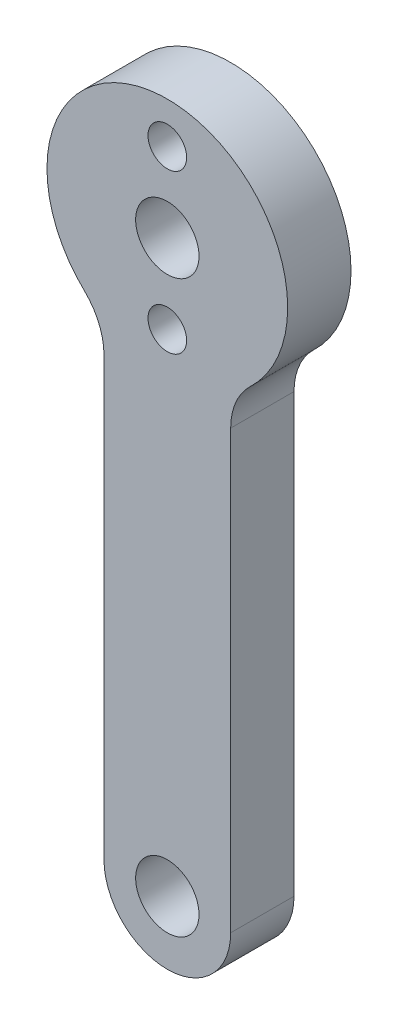
SolidWorks part; units mm, degrees
material "Thornel Mat VMA"
ref_plane "前视基准面" through (0, 0, 0) normal (0, 0, 1) x (1, 0, 0)
ref_plane "上视基准面" through (0, 0, 0) normal (0, 1, 0) x (1, 0, 0)
ref_plane "右视基准面" through (0, 0, 0) normal (1, 0, 0) x (0, 0, -1)
sketch "草图1" plane through (0, 0, 0) normal (0, 0, 1) x (1, 0, 0)
  line L0 (0, 0) -> (0, -45) construction
  line L1 (5, -8.0777) -> (5, -45)
  line L2 (-5, -8.0777) -> (-5, -45)
  arc A0 (5, -8.0777) -> (-5, -8.0777) centre (0, 0) ccw
  arc A2 (-5, -45) -> (5, -45) centre (0, -45) ccw
  point P3 (0, -25)
  dimension "D1" = 45
  dimension "D2" = 19
  dimension "D3" = 5
extrude "凸台-拉伸1" add sketch "草图1" along normal blind 5
sketch "草图3" plane through (0, 0, 5) normal (0, 0, 1) x (1, 0, 0)
  circle A0 centre (0, -45) radius 2.5
  dimension "D1" = 5
extrude "切除-拉伸1" cut sketch "草图3" against normal blind 24
sketch "草图4" plane through (0, 0, 5) normal (0, 0, 1) x (1, 0, 0)
  circle A0 centre (0, 0) radius 6.25 construction
  circle A1 centre (0, 6.25) radius 1.525
  circle A2 centre (0, -6.25) radius 1.525
  dimension "D1" = 12.5
  dimension "D2" = 3.05
extrude "切除-拉伸2" cut sketch "草图4" against normal blind 5
sketch "草图5" plane through (0, 0, 5) normal (0, 0, 1) x (1, 0, 0)
  circle A0 centre (0, 0) radius 2.5
  dimension "D1" = 5
extrude "切除-拉伸3" cut sketch "草图5" against normal blind 5
fillet "圆角1" radius 5 2 edges at (5, -8.0777, 2.5) (-5, -8.0777, 2.5)
